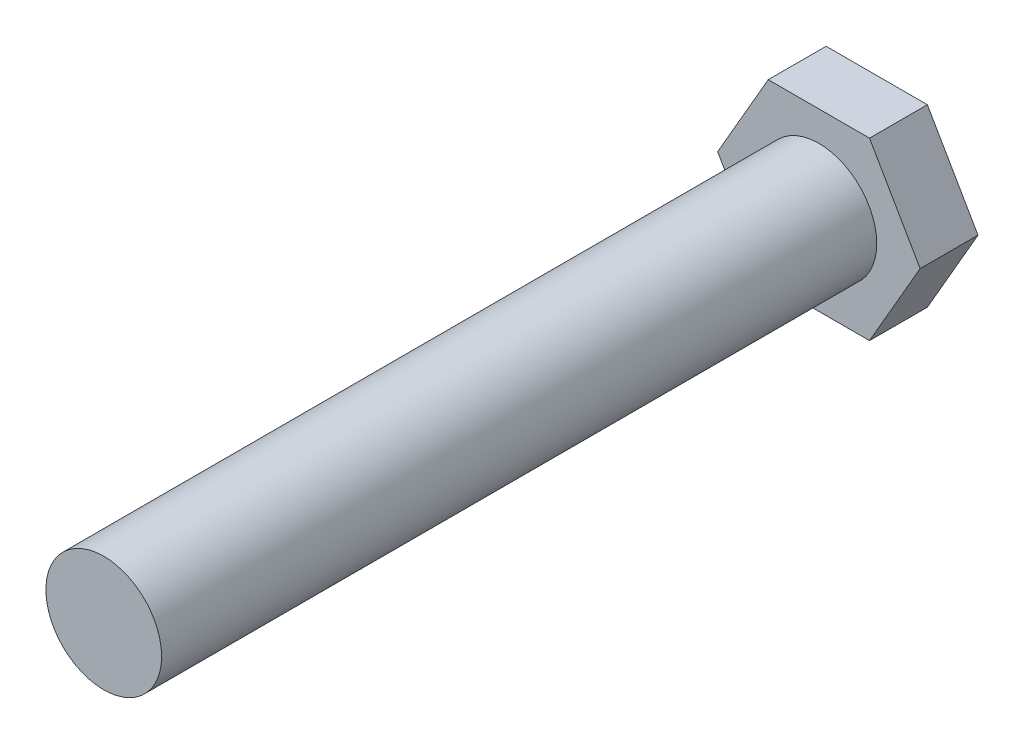
SolidWorks part; units mm, degrees
ref_plane "Front Plane" through (0, 0, 0) normal (0, 0, 1) x (1, 0, 0)
ref_plane "Top Plane" through (0, 0, 0) normal (0, 1, 0) x (1, 0, 0)
ref_plane "Right Plane" through (0, 0, 0) normal (1, 0, 0) x (0, 0, -1)
sketch "Sketch1" plane through (0, 0, 0) normal (0, 0, 1) x (1, 0, 0)
  line L1 (22.225, 0) -> (11.1125, 19.2474)
  line L2 (11.1125, 19.2474) -> (-11.1125, 19.2474)
  line L3 (-11.1125, 19.2474) -> (-22.225, 0)
  line L4 (-22.225, 0) -> (-11.1125, -19.2474)
  line L5 (-11.1125, -19.2474) -> (11.1125, -19.2474)
  line L6 (11.1125, -19.2474) -> (22.225, 0)
  circle A0 centre (0, 0) radius 19.2474 construction
  dimension "D1" = 44.45
extrude "Boss-Extrude1" add sketch "Sketch1" along normal blind 12.7
sketch "Sketch2" plane through (0, 0, 12.7) normal (0, 0, 1) x (1, 0, 0)
  circle A0 centre (0, 0) radius 12.7
  dimension "D1" = 25.4
extrude "Boss-Extrude2" add sketch "Sketch2" along normal blind 156.972
